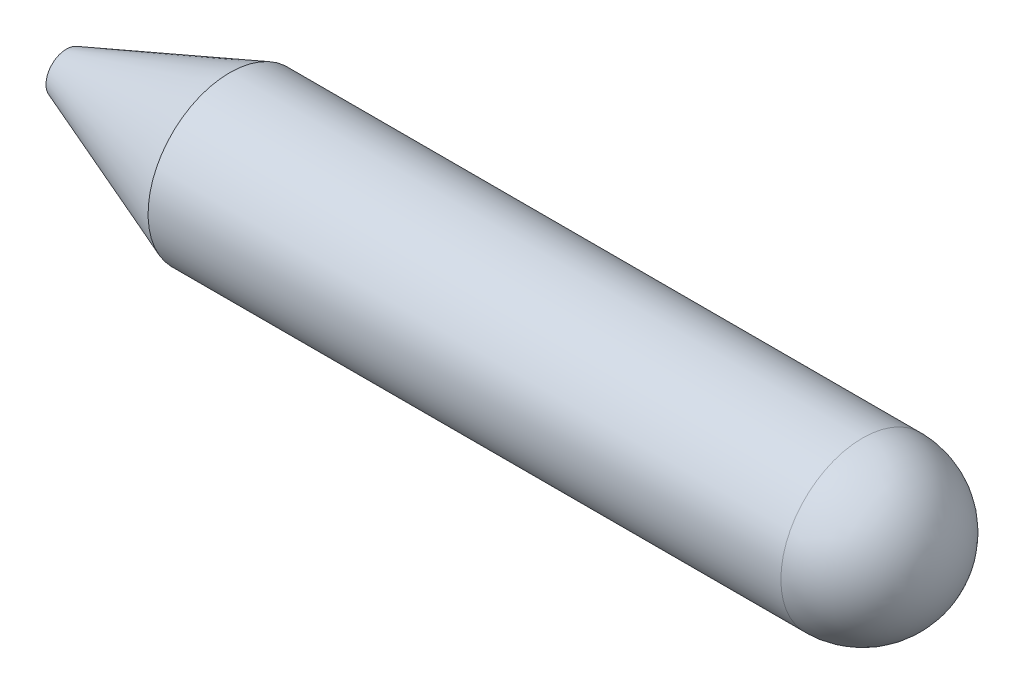
SolidWorks part; units mm, degrees
ref_plane "Plan de face" through (0, 0, 0) normal (0, 0, 1) x (1, 0, 0)
ref_plane "Plan de dessus" through (0, 0, 0) normal (0, 1, 0) x (1, 0, 0)
ref_plane "Plan de droite" through (0, 0, 0) normal (1, 0, 0) x (0, 0, -1)
sketch "Sketch2" plane through (0, 0, 0) normal (0, 0, 1) x (1, 0, 0)
  line L0 (-21.5, 0) -> (-21.5, 0.5)
  line L1 (0, 0) -> (-21.5, 0)
  line L3 (-2, 2) -> (-17.5, 2)
  line L5 (-21.5, 0.5) -> (-17.5, 2)
  arc A0 (0, 0) -> (-2, 2) centre (-2, 0) ccw
  dimension "D5" = 2
  dimension "D1" = 15.5
  dimension "D2" = 21.5
  dimension "D3" = 0.5
  dimension "D4" = 2
  dimension "D6" = 4
revolve "Revolve1" add sketch "Sketch2" angle 360 about L1
